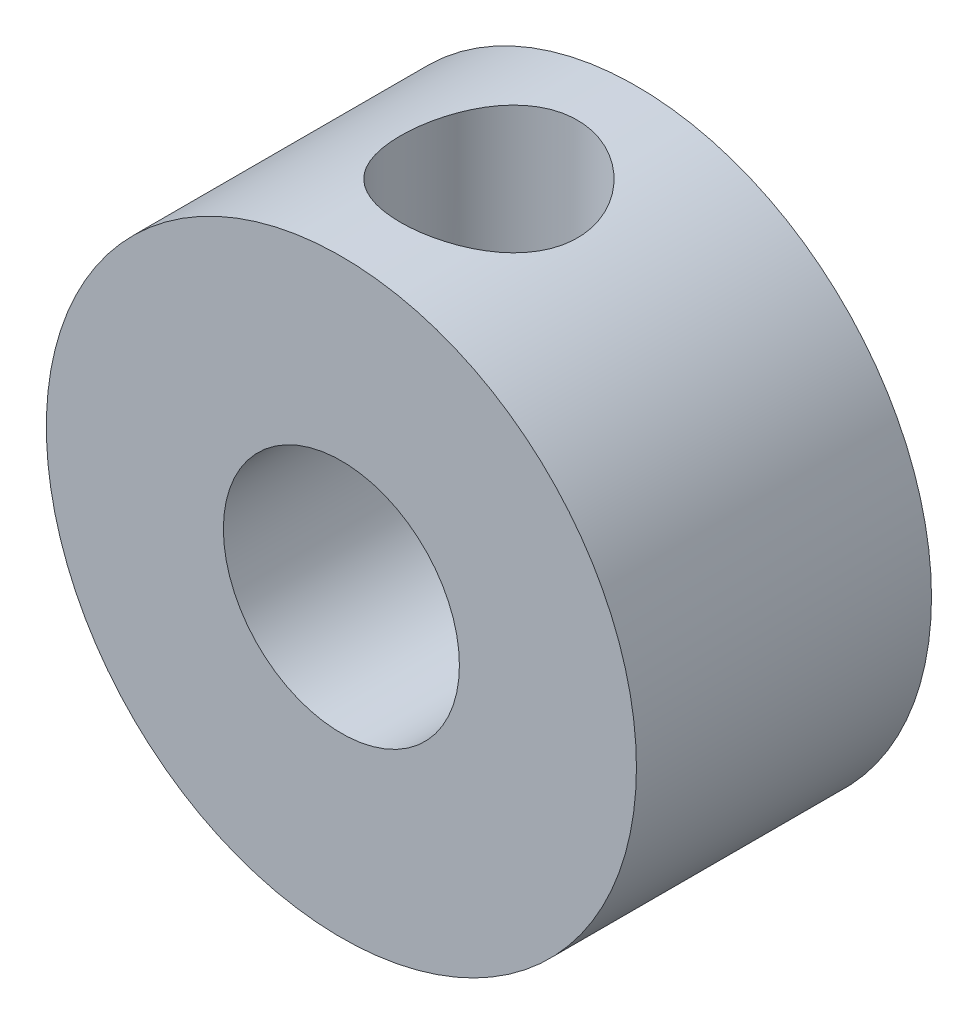
SolidWorks part; units mm, degrees
ref_plane "Front" through (0, 0, 0) normal (0, 0, 1) x (1, 0, 0)
ref_plane "Top" through (0, 0, 0) normal (0, 1, 0) x (1, 0, 0)
ref_plane "Right" through (0, 0, 0) normal (1, 0, 0) x (0, 0, -1)
sketch "Sketch1" plane through (0, 0, 0) normal (0, 0, 1) x (1, 0, 0)
  circle A0 centre (0, 0) radius 2
  circle A1 centre (0, 0) radius 5
  dimension "D1" = 4
  dimension "D2" = 10
extrude "Boss-Extrude1" add sketch "Sketch1" along normal mid plane 5
ref_plane "Plane1" through (0, 5, 0) normal (0, 1, 0) x (1, 0, 0)
sketch "Sketch3" plane through (0, 5, 0) normal (0, 1, 0) x (1, 0, 0)
  circle A0 centre (0, 0) radius 1.5
  dimension "D1" = 3
extrude "Cut-Extrude1" cut sketch "Sketch3" against normal blind 5
